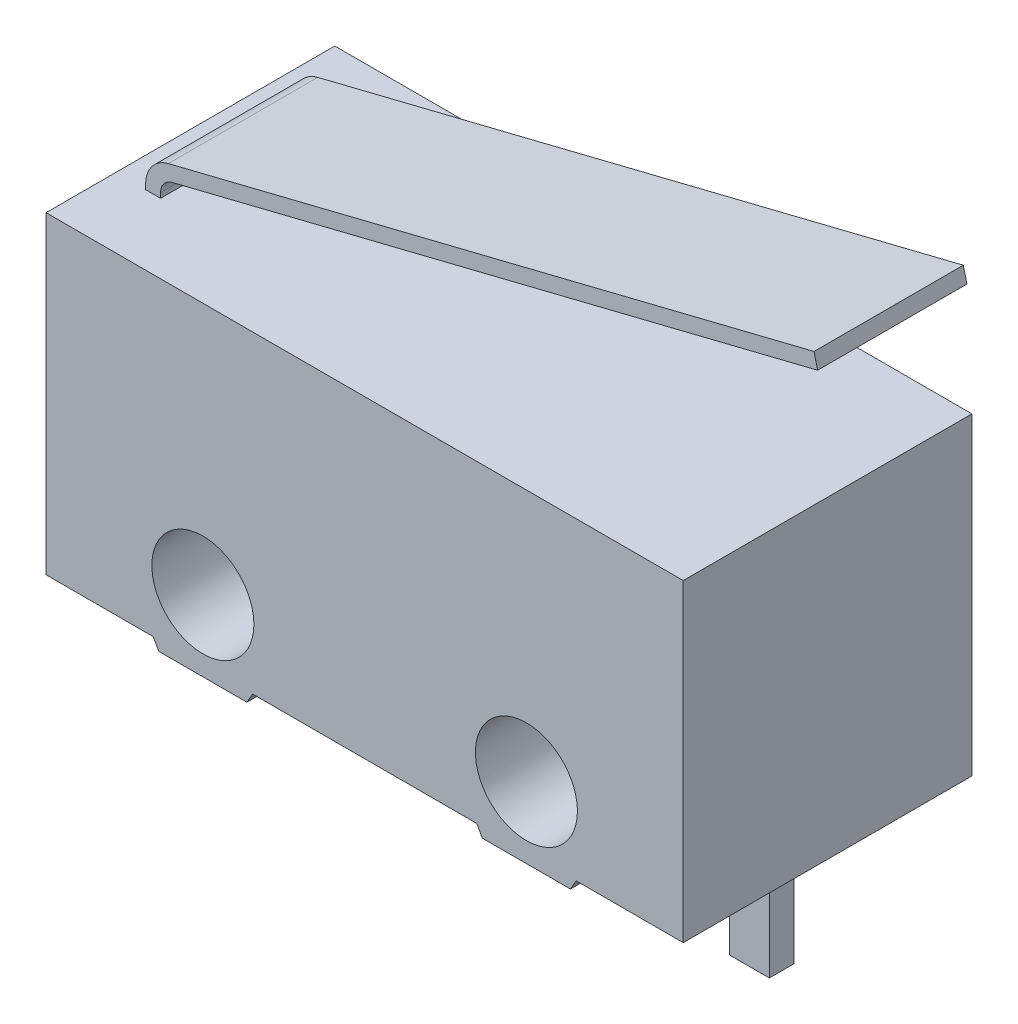
SolidWorks part; units mm, degrees
ref_plane "Front Plane" through (0, 0, 0) normal (0, 0, 1) x (1, 0, 0)
ref_plane "Top Plane" through (0, 0, 0) normal (0, 1, 0) x (1, 0, 0)
ref_plane "Right Plane" through (0, 0, 0) normal (1, 0, 0) x (0, 0, -1)
sketch "Sketch1" plane through (0, 0, 0) normal (0, 1, 0) x (1, 0, 0)
  line L0 (-6.4, 2.9) -> (6.4, -2.9) construction
  line L1 (-6.4, 2.9) -> (6.4, 2.9)
  line L2 (-6.4, 2.9) -> (-6.4, -2.9)
  line L3 (-6.4, -2.9) -> (6.4, -2.9)
  line L4 (6.4, 2.9) -> (6.4, -2.9)
  point P4 (-12.8288, 1.3763)
  point P5 (0, 0)
  dimension "D1" = 5.8
  dimension "D2" = 12.8
extrude "Boss-Extrude1" add sketch "Sketch1" along normal blind 6.5
sketch "Sketch2" plane through (0, 0, 2.9) normal (0, 0, 1) x (1, 0, 0)
  line L0 (0, 0) -> (0, 6.5) construction
  line L1 (-6.4, 0.2) -> (-4.25, 0.2)
  line L2 (-4.25, 0.2) -> (-4.1345, 0)
  line L3 (4.1345, 0) -> (6.4, 0)
  line L4 (-6.4, 0) -> (6.4, 0)
  line L5 (6.4, 0) -> (6.4, 6.5)
  line L6 (6.4, 6.5) -> (-6.4, 6.5)
  line L7 (-6.4, 6.5) -> (-6.4, 0)
  line L8 (-6.4, 0) -> (-4.1345, 0)
  line L9 (6.4, 0) -> (6.4, 0.2)
  line L10 (6.4, 6.5) -> (-6.4, 6.5) construction
  line L11 (-6.4, 0.2) -> (-6.4, 0)
  line L12 (6.4, 0.2) -> (4.25, 0.2)
  line L13 (4.25, 0.2) -> (4.1345, 0)
  line L14 (2.3655, 0) -> (2.25, 0.2)
  line L15 (-6.4, 0) -> (6.4, 0) construction
  line L16 (2.25, 0.2) -> (-2.25, 0.2)
  line L17 (-2.25, 0.2) -> (-2.3655, 0)
  line L18 (-2.3655, 0) -> (2.3655, 0)
  line L19 (3.25, 1.425) -> (3.25, 0) construction
  line L20 (-3.25, 1.425) -> (-3.25, 0) construction
  circle A0 centre (-3.25, 1.425) radius 1.025
  circle A1 centre (3.25, 1.425) radius 1.025
  point P12 (-3.25, 0.4)
  point P17 (-4.0967, 0)
  dimension "D3" = 2.05
  dimension "D2" = 6.5
  dimension "D4" = 0.4
  dimension "D5" = 0.2
  dimension "D6" = 2
  dimension "D7" = 120
  dimension "D1" = 0
extrude "Cut-Extrude1" cut sketch "Sketch2" against normal through all
sketch "Sketch3" plane through (0, 0.2, 0) normal (0, -1, 0) x (1, 0, 0)
  line L0 (-0.4, 0.25) -> (0.4, -0.25) construction
  line L1 (-0.4, 0.25) -> (0.4, 0.25)
  line L2 (-0.4, 0.25) -> (-0.4, -0.25)
  line L3 (-0.4, -0.25) -> (0.4, -0.25)
  line L4 (0.4, 0.25) -> (0.4, -0.25)
  line L5 (4.68, 0.25) -> (5.48, 0.25)
  line L6 (4.68, 0.25) -> (4.68, -0.25)
  line L7 (4.68, -0.25) -> (5.48, -0.25)
  line L8 (5.48, 0.25) -> (5.48, -0.25)
  line L9 (-5.48, 0.25) -> (-4.68, 0.25)
  line L10 (-5.48, 0.25) -> (-5.48, -0.25)
  line L11 (-5.48, -0.25) -> (-4.68, -0.25)
  line L12 (-4.68, 0.25) -> (-4.68, -0.25)
  line L13 (0, 0) -> (0, 0.25) construction
  line L14 (-5.08, 0.25) -> (-5.08, -0.25) construction
  line L15 (5.08, 0.25) -> (5.08, -0.25) construction
  point P12 (0, 0)
  dimension "D1" = 0.5
  dimension "D2" = 0.8
  dimension "D3" = 10.16
extrude "Boss-Extrude2" add sketch "Sketch3" along normal blind 2.4
sketch "Sketch4" plane through (0, 0, 0) normal (0, 0, 1) x (1, 0, 0)
  line L0 (-5.8, 6.5) -> (-5.8, 6.6)
  line L1 (-6.4, 6.5) -> (6.4, 6.5) construction
  line L3 (-5.3444, 7.1824) -> (7.6278, 10.4)
  line L4 (7.6278, 10.4) -> (7.7, 10.1088)
  line L5 (7.7, 10.1088) -> (-5.2722, 6.8912)
  line L7 (-5.5, 6.6) -> (-5.5, 6.5)
  line L8 (-5.5, 6.5) -> (-5.8, 6.5)
  line L10 (6.4, 6.5) -> (6.4, 0.2) construction
  arc A0 (-5.2722, 6.8912) -> (-5.5, 6.6) centre (-5.2, 6.6) ccw
  arc A1 (-5.3444, 7.1824) -> (-5.8, 6.6) centre (-5.2, 6.6) ccw
  point P4 (1.5281, 10.13)
  point P12 (0, 0)
  point P13 (-5.4182, 6.7048)
  point P16 (-5.2651, 7.2356)
  point P17 (7.1214, 10.1095)
  dimension "D2" = 0.1
  dimension "D5" = 0.6
  dimension "D1" = 0.3
  dimension "D3" = 0.6
  dimension "D4" = 10.4
  dimension "D6" = 1.3
extrude "Boss-Extrude3" add sketch "Sketch4" along normal mid plane 3
